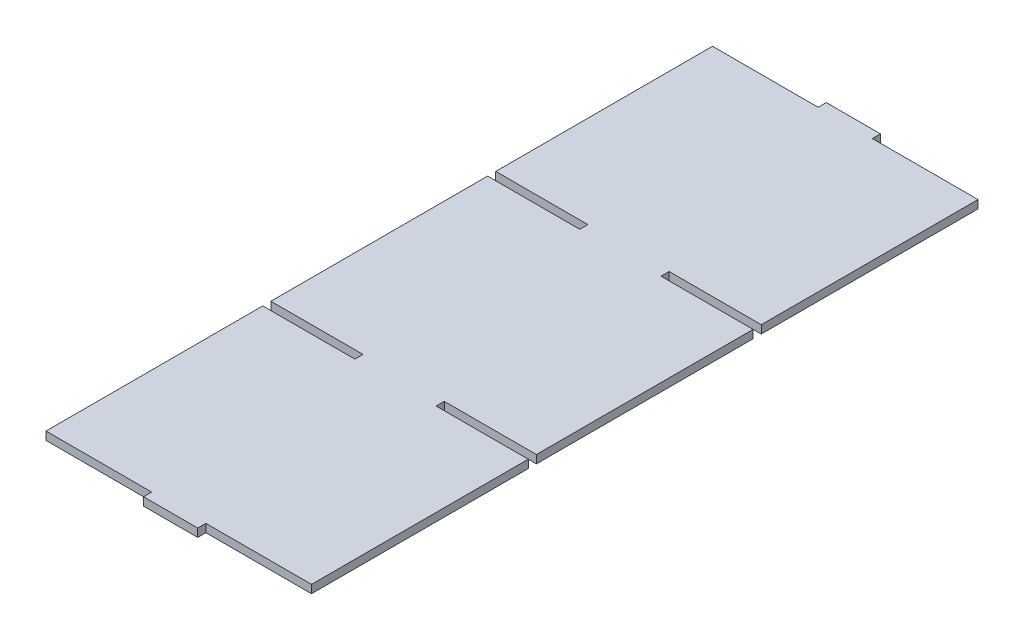
SolidWorks part; units mm, degrees
ref_plane "Front Plane" through (0, 0, 0) normal (0, 0, 1) x (1, 0, 0)
ref_plane "Top Plane" through (0, 0, 0) normal (0, 1, 0) x (1, 0, 0)
ref_plane "Right Plane" through (0, 0, 0) normal (1, 0, 0) x (0, 0, -1)
sketch "Sketch1" plane through (0, 0, 0) normal (0, 1, 0) x (1, 0, 0)
  line L0 (0, 0) -> (0, 3)
  line L1 (0, 3) -> (-39, 3)
  line L2 (-39, 3) -> (-39, 83)
  line L3 (-39, 83) -> (-5, 83)
  line L4 (-5, 83) -> (-5, 86)
  line L5 (-5, 86) -> (-39, 86)
  line L6 (-39, 86) -> (-39, 166)
  line L7 (-39, 166) -> (-5, 166)
  line L8 (-5, 166) -> (-5, 169)
  line L9 (-5, 169) -> (-39, 169)
  line L10 (-39, 169) -> (-39, 249)
  line L11 (-39, 249) -> (0, 249)
  line L12 (0, 249) -> (0, 252)
  line L13 (0, 252) -> (20, 252)
  line L14 (20, 252) -> (20, 249)
  line L15 (20, 249) -> (59, 249)
  line L16 (59, 249) -> (59, 169)
  line L17 (59, 169) -> (25, 169)
  line L18 (25, 169) -> (25, 166)
  line L19 (25, 166) -> (59, 166)
  line L20 (59, 166) -> (59, 86)
  line L21 (59, 86) -> (25, 86)
  line L22 (25, 86) -> (25, 83)
  line L23 (25, 83) -> (59, 83)
  line L24 (59, 83) -> (59, 3)
  line L25 (59, 3) -> (20, 3)
  line L26 (20, 3) -> (20, 0)
  line L27 (20, 0) -> (0, 0)
  line L28 (10, 0) -> (10, 252) construction
  dimension "D1" = 20
  dimension "D2" = 3
  dimension "D3" = 80
  dimension "D4" = 3
  dimension "D5" = 80
  dimension "D6" = 3
  dimension "D7" = 30
  dimension "D8" = 30
  dimension "D9" = 80
  dimension "D10" = 3
  dimension "D11" = 98
extrude "Boss-Extrude1" add sketch "Sketch1" along normal blind 3 contours L24 L25 L26 L27 L0 L1 L2 L3 L4 L5 L6 L7 L8 L9 L10 L11 L12 L13 L14 L15 L16 L17 L18 L19 L20 L21 L22 L23
